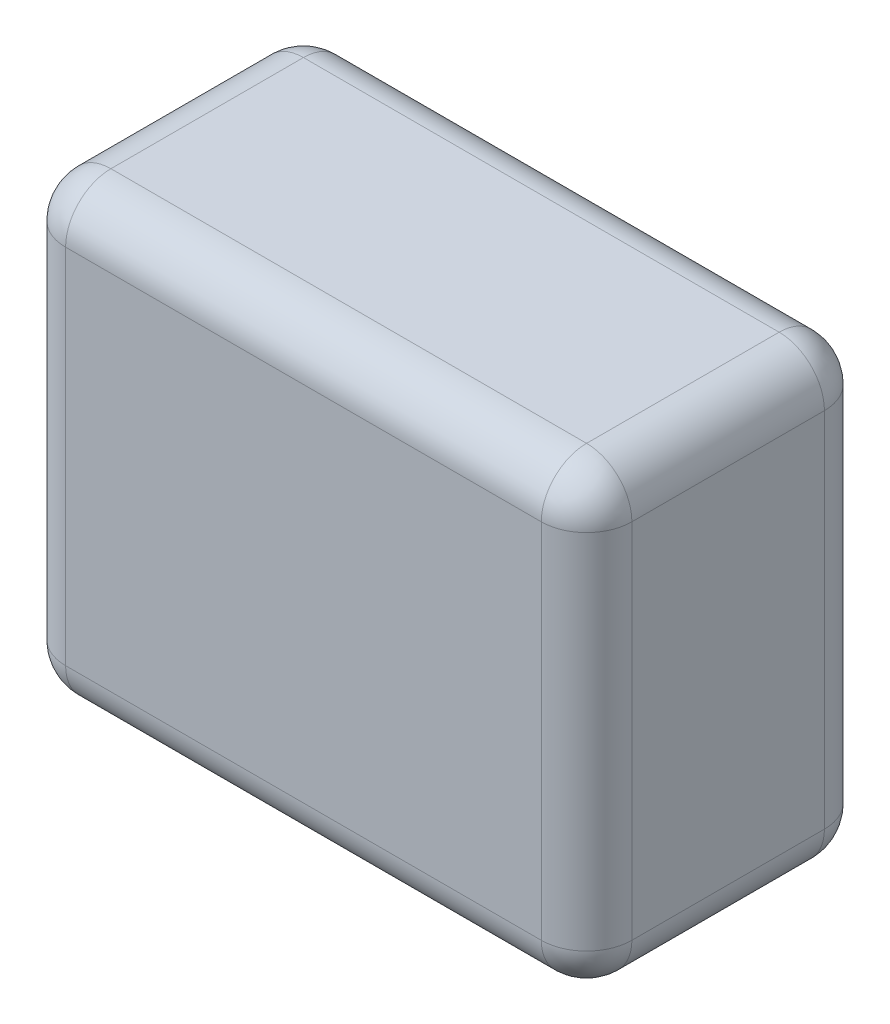
SolidWorks part; units mm, degrees
ref_plane "Front Plane" through (0, 0, 0) normal (0, 0, 1) x (1, 0, 0)
ref_plane "Top Plane" through (0, 0, 0) normal (0, 1, 0) x (1, 0, 0)
ref_plane "Right Plane" through (0, 0, 0) normal (1, 0, 0) x (0, 0, -1)
sketch "Sketch1" plane through (0, 0, 0) normal (0, 0, 1) x (1, 0, 0)
  line L1 (-25, 20) -> (25, 20)
  line L2 (-25, 20) -> (-25, -20)
  line L3 (-25, -20) -> (25, -20)
  line L4 (25, 20) -> (25, -20)
  line L5 (-25, 20) -> (25, -20) construction
  line L6 (-25, -20) -> (25, 20) construction
  point P0 (0, 0)
  dimension "D1" = 50
  dimension "D2" = 40
extrude "Boss-Extrude1" add sketch "Sketch1" along normal blind 25
fillet "Fillet1" radius 4 12 edges at (25, 0, 0) (0, 20, 0) (-25, 0, 0) (0, -20, 0) (25, 0, 25) (-25, 0, 25) (0, -20, 25) (25, -20, 12.5) (-25, -20, 12.5) (-25, 20, 12.5) (25, 20, 12.5) (0, 20, 25)
